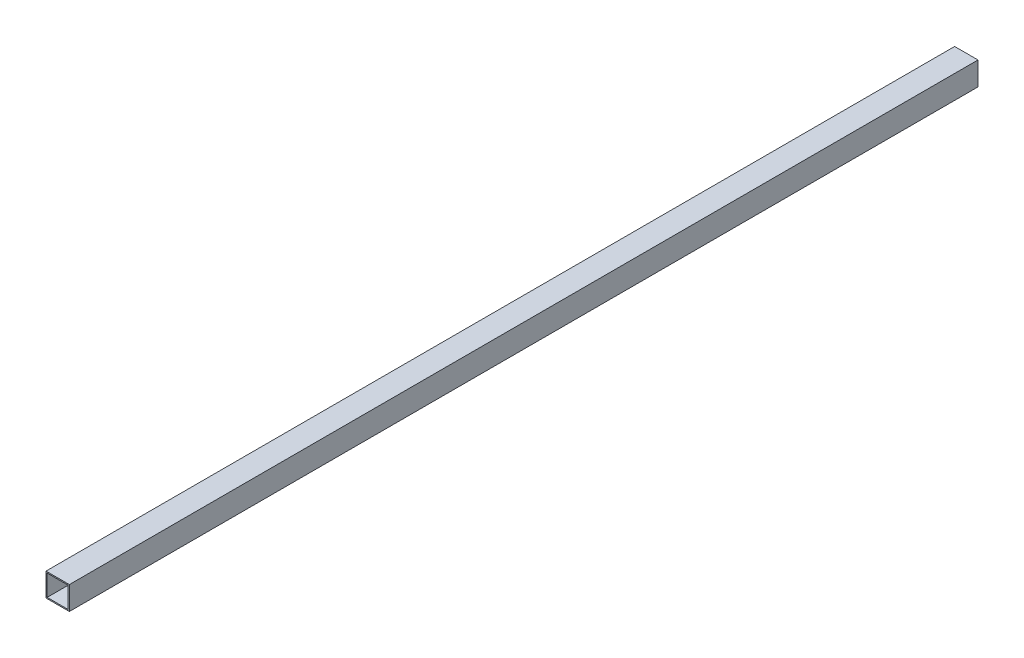
SolidWorks part; units mm, degrees
ref_plane "Front Plane" through (0, 0, 0) normal (0, 0, 1) x (1, 0, 0)
ref_plane "Top Plane" through (0, 0, 0) normal (0, 1, 0) x (1, 0, 0)
ref_plane "Right Plane" through (0, 0, 0) normal (1, 0, 0) x (0, 0, -1)
sketch "Sketch1" plane through (0, 0, 0) normal (0, 0, 1) x (1, 0, 0)
  line L5 (-15.875, 15.875) -> (15.875, 15.875)
  line L6 (-15.875, 15.875) -> (-15.875, -15.875)
  line L11 (-15.875, -15.875) -> (15.875, -15.875)
  line L12 (15.875, 15.875) -> (15.875, -15.875)
  line L13 (-15.875, 15.875) -> (15.875, -15.875) construction
  line L14 (-15.875, -15.875) -> (15.875, 15.875) construction
  line L15 (-14.2875, 14.2875) -> (14.2875, 14.2875)
  line L16 (-14.2875, 14.2875) -> (-14.2875, -14.2875)
  line L17 (-14.2875, -14.2875) -> (14.2875, -14.2875)
  line L18 (14.2875, 14.2875) -> (14.2875, -14.2875)
  line L19 (-14.2875, 14.2875) -> (14.2875, -14.2875) construction
  line L20 (-14.2875, -14.2875) -> (14.2875, 14.2875) construction
  point P0 (0, 0)
  point P6 (0, 0)
  dimension "D1" = 31.75
  dimension "D2" = 31.75
  dimension "D3" = 1.5875
extrude "Boss-Extrude1" add sketch "Sketch1" along normal blind 1235
